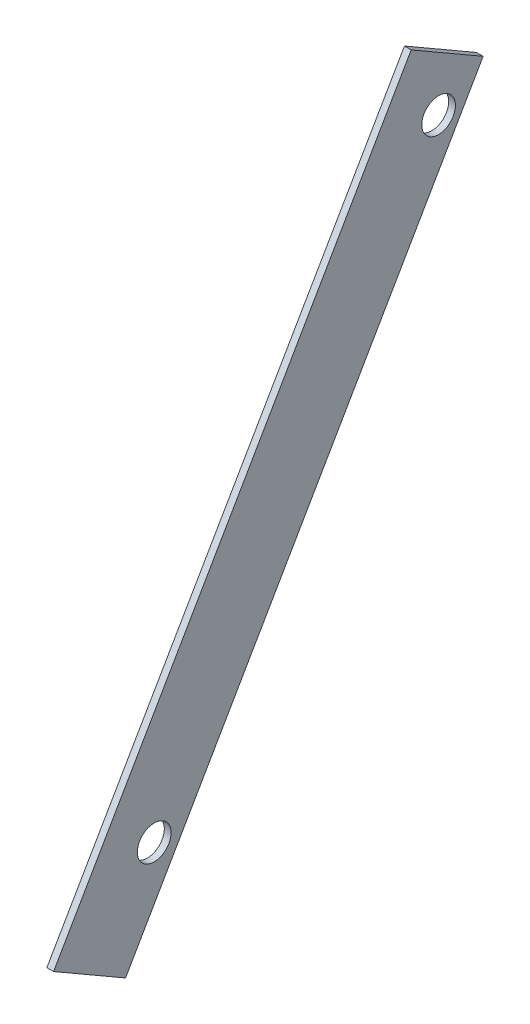
SolidWorks part; units mm, degrees
ref_plane "Front Plane" through (0, 0, 0) normal (0, 0, 1) x (1, 0, 0)
ref_plane "Top Plane" through (0, 0, 0) normal (0, 1, 0) x (1, 0, 0)
ref_plane "Right Plane" through (0, 0, 0) normal (1, 0, 0) x (0, 0, -1)
sketch "Sketch1" plane through (0, 0, 0) normal (1, 0, 0) x (0, 0, -1)
  line L0 (0, 0) -> (-1061.95, -1839.3514)
  line L1 (0, 0) -> (-213.7351, 123.4)
  line L2 (-213.7351, 123.4) -> (-1275.6851, -1715.9514)
  line L3 (-1061.95, -1839.3514) -> (-1275.6851, -1715.9514)
  dimension "D1" = 2123.9
  dimension "D2" = 246.8
extrude "Boss-Extrude1" add sketch "Sketch1" along normal blind 20
sketch "Sketch2" plane through (0, 0, 0) normal (-1, 0, 0) x (0, 0, 1)
  circle A0 centre (976.8885, -1533.2787) radius 50
  circle A1 centre (132.3687, -81.5655) radius 50
extrude "Cut-Extrude4" cut sketch "Sketch2" against normal through all contours A0
sketch "Sketch3" plane through (20, 0, 0) normal (1, 0, 0) x (0, 0, -1)
  circle A0 centre (-132.3803, -85.0965) radius 50
  dimension "D1" = 100
extrude "Cut-Extrude6" cut sketch "Sketch3" against normal through all
